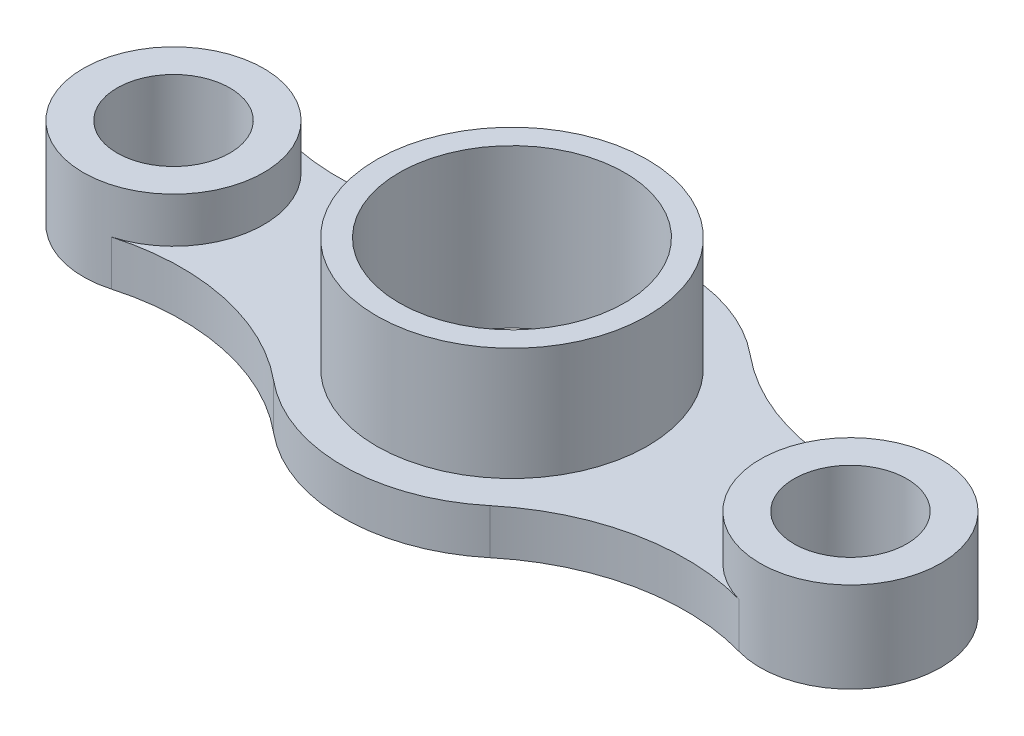
SolidWorks part; units mm, degrees
ref_plane "Front Plane" through (0, 0, 0) normal (0, 0, 1) x (1, 0, 0)
ref_plane "Top Plane" through (0, 0, 0) normal (0, 1, 0) x (1, 0, 0)
ref_plane "Right Plane" through (0, 0, 0) normal (1, 0, 0) x (0, 0, -1)
sketch "Sketch1" plane through (0, 0, 0) normal (0, 1, 0) x (1, 0, 0)
  line L0 (-150, 0) -> (91.4535, 0) construction
  line L1 (0, 90.0038) -> (0, -112.8484) construction
  arc A0 (-47.8929, -57.7172) -> (47.8929, -57.7172) centre (0, 0) ccw
  arc A1 (-139.0714, 38.4781) -> (-139.0714, -38.4781) centre (-150, 0) ccw
  arc A2 (-139.0714, 38.4781) -> (-47.8929, 57.7172) centre (-111.75, 134.6734) ccw
  arc A3 (-139.0714, -38.4781) -> (-47.8929, -57.7172) centre (-111.75, -134.6734) cw
  arc A4 (139.0714, 38.4781) -> (139.0714, -38.4781) centre (150, 0) cw
  arc A5 (139.0714, -38.4781) -> (47.8929, -57.7172) centre (111.75, -134.6734) ccw
  arc A6 (139.0714, 38.4781) -> (47.8929, 57.7172) centre (111.75, 134.6734) cw
  arc A7 (47.8929, 57.7172) -> (-47.8929, 57.7172) centre (0, 0) ccw
  dimension "D1" = 150
  dimension "D2" = 80
  dimension "D3" = 150
  dimension "D4" = 200
extrude "Boss-Extrude1" add sketch "Sketch1" along normal blind 20
sketch "Sketch2" plane through (0, 20, 0) normal (0, 1, 0) x (1, 0, 0)
  circle A0 centre (0, 0) radius 60
extrude "Boss-Extrude2" add sketch "Sketch2" along normal blind 50
sketch "Sketch3" plane through (0, 20, 0) normal (0, 1, 0) x (1, 0, 0)
  circle A0 centre (-150, 0) radius 40
  circle A1 centre (150, 0) radius 40
extrude "Boss-Extrude3" add sketch "Sketch3" along normal blind 20
sketch "Sketch4" plane through (0, 70, 0) normal (0, 1, 0) x (1, 0, 0)
  circle A0 centre (0, 0) radius 50
  circle A1 centre (-150, 0) radius 25
  circle A2 centre (150, 0) radius 25
extrude "Cut-Extrude1" cut sketch "Sketch4" against normal up to surface (70 mm away) up to face at (0, 0, 0)
